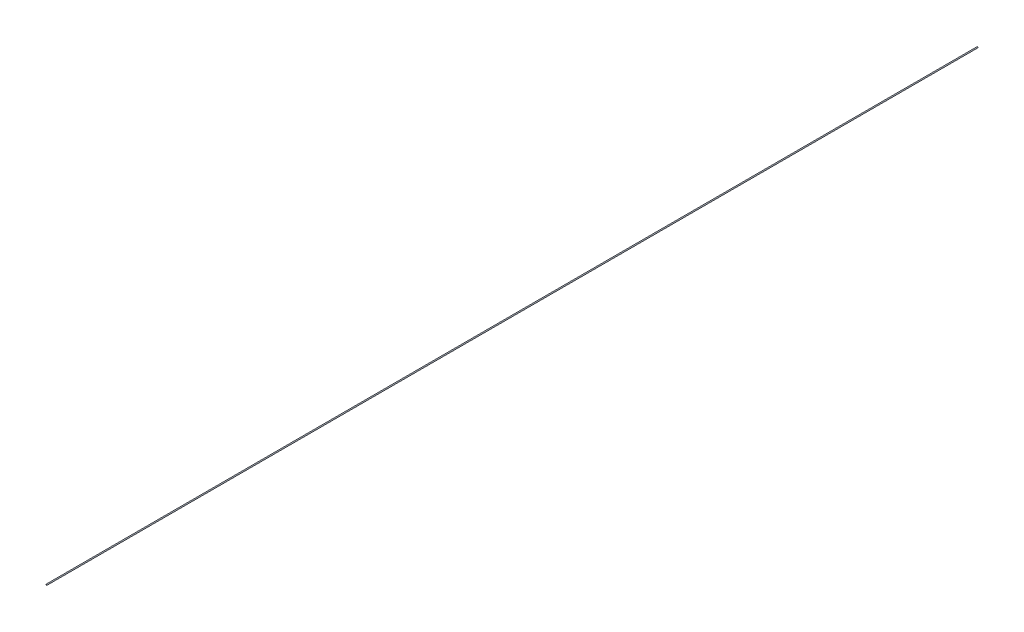
SolidWorks part; units mm, degrees
ref_plane "前视基准面" through (0, 0, 0) normal (0, 0, 1) x (1, 0, 0)
ref_plane "上视基准面" through (0, 0, 0) normal (0, 1, 0) x (1, 0, 0)
ref_plane "右视基准面" through (0, 0, 0) normal (1, 0, 0) x (0, 0, -1)
sketch "草图1" plane through (0, 0, 0) normal (0, 0, 1) x (1, 0, 0)
  circle A0 centre (0, 0) radius 0.6
extrude "凸台-拉伸1" add sketch "草图1" along normal blind 1092.962 contours A0
